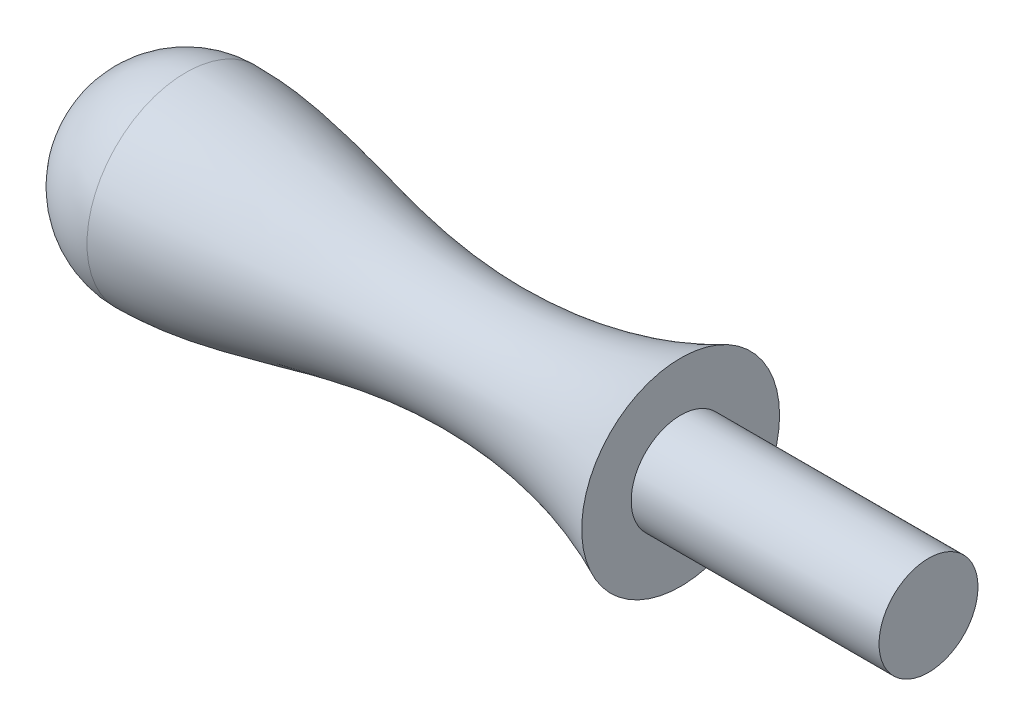
SolidWorks part; units mm, degrees
material "ABS"
ref_plane "Front Plane" through (0, 0, 0) normal (0, 0, 1) x (1, 0, 0)
ref_plane "Top Plane" through (0, 0, 0) normal (0, 1, 0) x (1, 0, 0)
ref_plane "Right Plane" through (0, 0, 0) normal (1, 0, 0) x (0, 0, -1)
sketch "Sketch1" plane through (0, 0, 0) normal (0, 1, 0) x (1, 0, 0)
  line L0 (0, 0) -> (-31.75, 0) construction
  line L1 (0, 6.35) -> (0, 0)
  line L2 (-38.1, 0) -> (-31.75, 0) construction
  line L3 (-31.75, 0) -> (0, 0)
  line L4 (-31.75, 6.35) -> (-31.75, 0) construction
  line L5 (-31.75, 6.35) -> (-36.8319, 6.35) construction
  line L6 (-38.1, 0) -> (-31.75, 0)
  arc A0 (-38.1, 0) -> (-31.75, 6.35) centre (-31.75, 0) cw
  spline S0 degree 3 poles (0, 6.35) (-5.7502, 3.6631) (-16.8937, 2.7636) (-27.1705, 6.35) (-31.75, 6.35) knots 0 0 0 0 0.57953 1 1 1 1
  dimension "D1" = 38.1
  dimension "D2" = 6.35
  dimension "D3" = 6.35
revolve "Revolve1" add sketch "Sketch1" angle 360 about L0
sketch "Sketch2" plane through (0, 0, 0) normal (1, 0, 0) x (0, 0, -1)
  circle A0 centre (0, 0) radius 3.175
  dimension "D1" = 6.35
extrude "Boss-Extrude1" add sketch "Sketch2" along normal blind 15.9091
